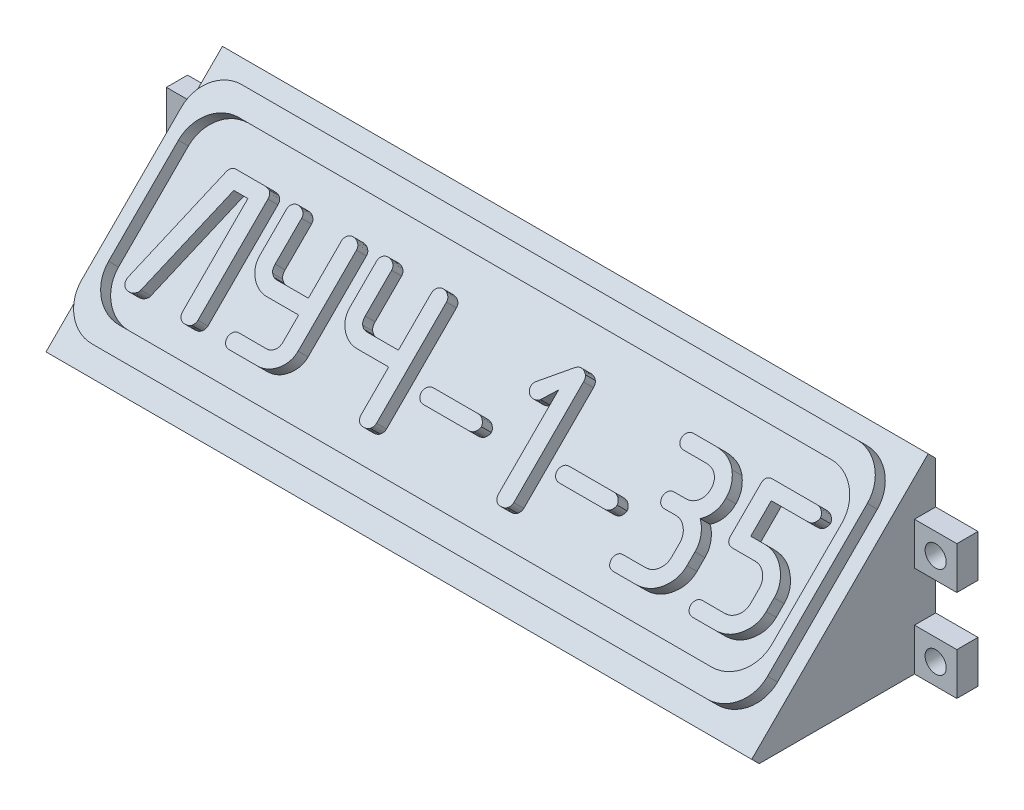
SolidWorks part; units mm, degrees
ref_plane "Спереди" through (0, 0, 0) normal (0, 0, 1) x (1, 0, 0)
ref_plane "Сверху" through (0, 0, 0) normal (0, 1, 0) x (1, 0, 0)
ref_plane "Справа" through (0, 0, 0) normal (1, 0, 0) x (0, 0, -1)
sketch "Эскиз1" plane through (0, 0, 0) normal (0, 1, 0) x (1, 0, 0)
  line L0 (0, 0) -> (100, 0)
  line L1 (0, 0) -> (-100, 0)
  line L2 (-100, 0) -> (-100, 50)
  line L3 (-100, 50) -> (-92, 50)
  line L4 (-92, 50) -> (-92, 8)
  line L5 (-92, 8) -> (92, 8)
  line L6 (92, 8) -> (92, 50)
  line L7 (92, 50) -> (100, 50)
  line L8 (100, 50) -> (100, 0)
extrude "Бобышка-Вытянуть1" add sketch "Эскиз1" along normal blind 50
ref_plane "Плоскость1" through (100, 0, 0) normal (1, 0, 0) x (0, 0, -1)
sketch "Эскиз2" plane through (100, 0, 0) normal (1, 0, 0) x (0, 0, -1)
  line L0 (0, 0) -> (0, 50)
  line L1 (0, 50) -> (50, 50)
  line L2 (50, 50) -> (0, 0)
extrude "Вырез-Вытянуть1" cut sketch "Эскиз2" against normal through all
ref_plane "Плоскость2" through (0, 0, 0) normal (0, 0.7071, 0.7071) x (1, 0, 0)
sketch "Эскиз3" plane through (0, 0, 0) normal (0, 0.7071, 0.7071) x (1, 0, 0)
  line L0 (-100, 70.7107) -> (-100, 0)
  line L1 (-100, 0) -> (100, 0)
  line L2 (100, -27.5) -> (100, 27.5) construction
  line L3 (-100, 0) -> (100, 0) construction
  line L4 (100, 0) -> (100, 70.7107)
  line L5 (100, 70.7107) -> (-100, 70.7107)
extrude "Бобышка-Вытянуть2" add sketch "Эскиз3" along normal blind 3
ref_plane "Плоскость3" through (0, 2.1213, 2.1213) normal (0, 0.7071, 0.7071) x (1, 0, 0)
sketch "Эскиз4" plane through (0, 2.1213, 2.1213) normal (0, 0.7071, 0.7071) x (1, 0, 0)
  text T0 "ЛУЧ-1-35" font "GOST type B" height 32
extrude "Бобышка-Вытянуть3" add sketch "Эскиз4" along normal blind 4
sketch "Эскиз5" plane through (0, 2.1213, 2.1213) normal (0, 0.7071, 0.7071) x (1, 0, 0)
  line L2 (-98.4297, 66) -> (-98.4297, 6)
  line L3 (-95, 12) -> (93, 12)
  line L4 (93, 12) -> (93, 60)
  line L5 (93, 60) -> (-95, 60)
  line L6 (-95, 60) -> (-95, 12)
  line L7 (-98.4297, 6) -> (96, 6)
  line L8 (96, 6) -> (96, 66)
  line L10 (-98.4297, 66) -> (96, 66)
extrude "Бобышка-Вытянуть4" add sketch "Эскиз5" along normal blind 4
fillet "Скругление1" radius 10 8 edges at (-95, 12.0208, -4.9497) (-98.4297, 7.7782, -0.7071) (96, 7.7782, -0.7071) (93, 12.0208, -4.9497) (93, 45.9619, -38.8909) (96, 50.2046, -43.1335) (-95, 45.9619, -38.8909) (-98.4297, 50.2046, -43.1335)
ref_plane "Плоскость4" through (0, 0, -50) normal (0, 0, -1) x (-1, 0, 0)
sketch "Эскиз6" plane through (0, 0, -50) normal (0, 0, -1) x (-1, 0, 0)
  line L0 (-100, 0) -> (-112, 0)
  line L1 (-100, 28.6667) -> (-100, -28.6667) construction
  line L2 (-112, 0) -> (-112, 12)
  line L3 (-112, 12) -> (-100, 12)
  line L4 (-100, 12) -> (-100, 0)
  line L5 (100, 0) -> (112, 0)
  line L6 (-100, 26) -> (-100, 38)
  line L7 (-100, 38) -> (-112, 38)
  line L8 (-112, 38) -> (-112, 26)
  line L9 (-112, 26) -> (-100, 26)
  line L10 (100, 50) -> (100, 0) construction
  line L11 (112, 0) -> (112, 12)
  line L12 (112, 12) -> (100, 12)
  line L13 (100, 12) -> (100, 0)
  line L14 (100, 26) -> (112, 26)
  line L15 (112, 26) -> (112, 38)
  line L16 (112, 38) -> (100, 38)
  line L17 (100, 38) -> (100, 26)
  circle A0 centre (106, 32) radius 3
  circle A1 centre (106, 6) radius 3
  circle A2 centre (-106, 6) radius 3
  circle A3 centre (-106, 32) radius 3
  point P29 (0, 0)
  point P30 (0, 0)
  point P31 (0, 0)
  point P32 (0, 0)
extrude "Бобышка-Вытянуть5" add sketch "Эскиз6" against normal blind 6
